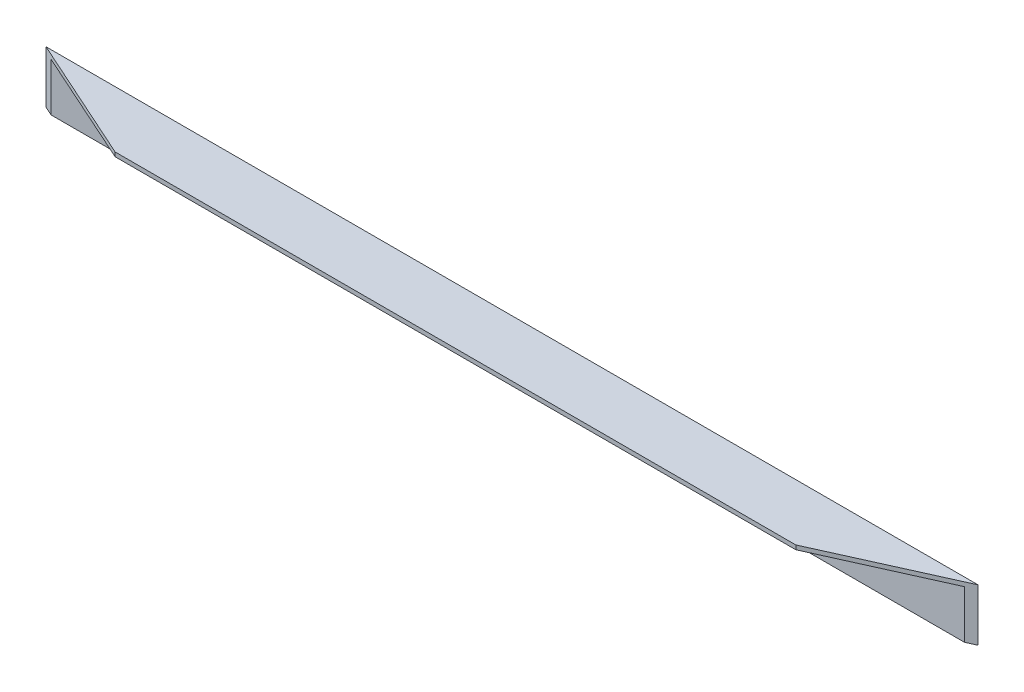
SolidWorks part; units mm, degrees
ref_plane "前视" through (0, 0, 0) normal (0, 0, 1) x (1, 0, 0)
ref_plane "上视" through (0, 0, 0) normal (0, 1, 0) x (1, 0, 0)
ref_plane "右视" through (0, 0, 0) normal (1, 0, 0) x (0, 0, -1)
sketch "草图1" plane through (0, 0, 0) normal (0, 0, 1) x (1, 0, 0)
  line L0 (0, 0) -> (0, 100) construction
  line L1 (-890, 0) -> (890, 0)
  line L2 (-890, 0) -> (-890, 100)
  line L3 (-890, 100) -> (890, 100)
  line L4 (890, 0) -> (890, 100)
  line L5 (1568.3745, 40) -> (890, 40) construction
  line L6 (890, 40) -> (0, 40) construction
  line L7 (468.717, 40) -> (338.4799, 40) construction
  line L8 (890, 40) -> (0, 40) construction
  line L9 (0, 72.6209) -> (0, 232.7989) construction
  line L10 (1000, 433.3131) -> (1000, -1026.6948) construction
  line L11 (-1000, 516.3236) -> (-1000, -1344.0878) construction
  dimension "D1" = 1780
  dimension "D2" = 100
  dimension "D3" = 40
extrude "基体-拉伸" add sketch "草图1" along normal blind 8
sketch "草图2" plane through (0, 0, 8) normal (0, 0, 1) x (1, 0, 0)
  line L0 (890, 0) -> (890, 100) construction
  line L1 (-890, 100) -> (890, 100)
  line L2 (-890, 100) -> (-890, 92)
  line L3 (-890, 92) -> (890, 92)
  line L4 (890, 100) -> (890, 92)
  dimension "D1" = 8
extrude "凸台-拉伸1" add sketch "草图2" along normal blind 100
sketch "草图3" plane through (0, 100, 0) normal (0, 1, 0) x (-1, 0, 0)
  line L0 (-890, 108) -> (890, 108) construction
  line L1 (-650, 108) -> (-890, 0)
  line L2 (-890, 0) -> (-890, 108)
  line L3 (-890, 108) -> (-650, 108)
  line L4 (0, -34.4051) -> (0, 171.3565) construction
  line L5 (890, 108) -> (650, 108)
  line L6 (890, 0) -> (890, 108)
  line L7 (650, 108) -> (890, 0)
  point P0 (-650, 108)
  dimension "D1" = 240
extrude "切除-拉伸1" cut sketch "草图3" against normal through all
